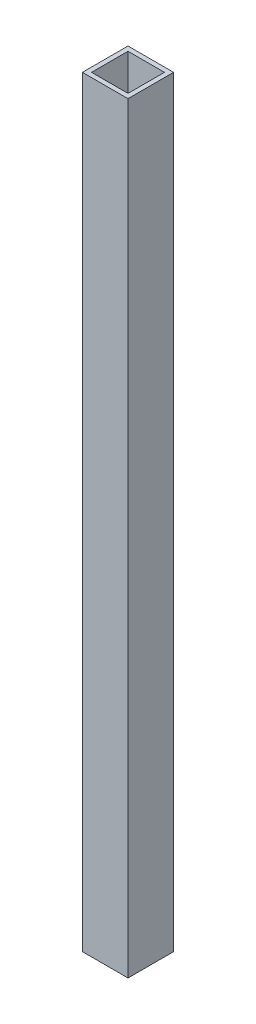
SolidWorks part; units mm, degrees
ref_plane "Front Plane" through (0, 0, 0) normal (0, 0, 1) x (1, 0, 0)
ref_plane "Top Plane" through (0, 0, 0) normal (0, 1, 0) x (1, 0, 0)
ref_plane "Right Plane" through (0, 0, 0) normal (1, 0, 0) x (0, 0, -1)
sketch "Sketch1" plane through (0, 0, 0) normal (0, 1, 0) x (1, 0, 0)
  line L0 (-10.16, 10.16) -> (10.16, 10.16)
  line L1 (-12.7, -12.7) -> (12.7, -12.7)
  line L2 (-12.7, -12.7) -> (-12.7, 12.7)
  line L3 (-12.7, 12.7) -> (12.7, 12.7)
  line L4 (12.7, -12.7) -> (12.7, 12.7)
  line L5 (-12.7, -12.7) -> (12.7, 12.7) construction
  line L6 (-12.7, 12.7) -> (12.7, -12.7) construction
  line L7 (10.16, -10.16) -> (10.16, 10.16)
  line L8 (-10.16, -10.16) -> (10.16, -10.16)
  line L9 (-10.16, -10.16) -> (-10.16, 10.16)
  point P0 (0, 0)
  dimension "D1" = 25.4
  dimension "D2" = 25.4
  dimension "D3" = 2.54
extrude "Boss-Extrude1" add sketch "Sketch1" along normal blind 424.18
